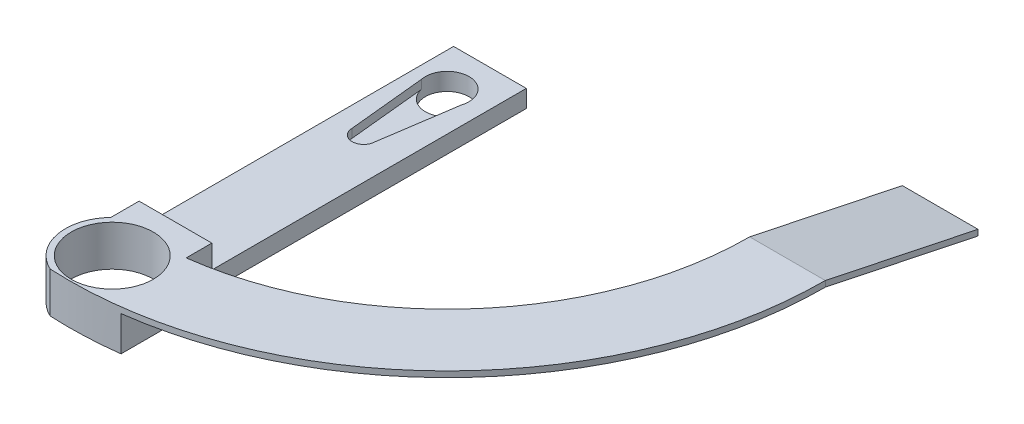
SolidWorks part; units mm, degrees
ref_plane "Front Plane" through (0, 0, 0) normal (0, 0, 1) x (1, 0, 0)
ref_plane "Top Plane" through (0, 0, 0) normal (0, 1, 0) x (1, 0, 0)
ref_plane "Right Plane" through (0, 0, 0) normal (1, 0, 0) x (0, 0, -1)
sketch "Sketch1" plane through (0, 0, 0) normal (0, 1, 0) x (1, 0, 0)
  line L4 (0, 0) -> (36.7696, -36.7696) construction
  line L6 (0, -63.5) -> (0, -51.6862) construction
  line L10 (6.6931, -1.4875) -> (6.6931, -51.5675)
  line L11 (-5.815, -3.0884) -> (-5.815, -52.0242)
  line L12 (-5.815, -3.0884) -> (-5.815, 3.9116)
  line L14 (6.6931, 3.9116) -> (6.6931, -1.4875)
  line L15 (45.9619, -45.9619) -> (61.1091, -61.1091) construction
  line L16 (48.0722, -19.8259) -> (60.0902, -24.7824)
  line L17 (6.6931, 3.9116) -> (6.6931, 6.9116)
  line L18 (6.6931, 6.9116) -> (-5.815, 6.9116)
  line L19 (-5.815, 6.9116) -> (-5.815, 3.9116)
  arc A0 (3.7159, -64.8937) -> (45.9619, -45.9619) centre (0, 0) ccw
  circle A2 centre (0, -57.5931) radius 7.0515
  arc A5 (-5.815, -52.0242) -> (-3.3524, -64.9135) centre (0, -57.5931) ccw
  arc A6 (36.7696, -36.7696) -> (6.6931, -51.5675) centre (0, 0) cw
  circle A7 centre (0, -57.5931) radius 8.0515 construction
  arc A8 (3.7159, -64.8937) -> (-3.3524, -64.9135) centre (0, 0) cw
  arc A9 (45.9619, -45.9619) -> (60.0902, -24.7824) centre (0, 0) ccw
  arc A10 (36.7696, -36.7696) -> (48.0722, -19.8259) centre (0, 0) ccw
  point P9 (0, 0)
  point P19 (0, 0)
  dimension "D1" = 1
extrude "Boss-Extrude1" add sketch "Sketch1" along normal blind 3
sketch "Sketch2" plane through (0, 3, 0) normal (0, 1, 0) x (1, 0, 0)
  line L2 (-5.815, -47.1607) -> (6.6931, -47.1607)
  line L4 (6.6931, -47.1607) -> (6.6931, -51.5675)
  line L6 (6.6931, -51.5675) -> (6.6931, 6.9116) construction
  line L7 (-5.815, -47.1607) -> (-5.815, -52.0242)
  line L8 (65, 0) -> (52, 0)
  arc A0 (-3.3524, -64.9135) -> (60.0902, -24.7824) centre (0, 0) ccw construction
  arc A1 (48.0722, -19.8259) -> (52, 0) centre (0, 0) ccw
  arc A2 (-3.3524, -64.9135) -> (60.0902, -24.7824) centre (0, 0) ccw
  circle A5 centre (0, -57.5931) radius 7.0515 construction
  circle A6 centre (0, -57.5931) radius 7.0515
  arc A7 (-5.815, -52.0242) -> (-3.3524, -64.9135) centre (0, -57.5931) ccw construction
  arc A8 (60.0902, -24.7824) -> (65, 0) centre (0, 0) ccw
  arc A9 (-5.815, -52.0242) -> (-3.3524, -64.9135) centre (0, -57.5931) ccw
  arc A10 (6.6931, -51.5675) -> (48.0722, -19.8259) centre (0, 0) ccw construction
  arc A11 (6.6931, -51.5675) -> (48.0722, -19.8259) centre (0, 0) ccw
  point P21 (0.4391, -47.1607)
extrude "Boss-Extrude2" add sketch "Sketch2" along normal blind 4
sketch "Sketch3" plane through (0, 3, 0) normal (0, 1, 0) x (1, 0, 0)
  circle A0 centre (0, 0) radius 3.75
sketch "Sketch4" plane through (0, 0, 0) normal (0, -1, 0) x (1, 0, 0)
  line L0 (0, -3.75) -> (0, 16) construction
  line L1 (3.75, 0) -> (1.65, 14)
  line L2 (-3.75, 0) -> (-2.35, 14)
  arc A0 (-3.75, 0) -> (3.75, 0) centre (0, 0) ccw
  arc A1 (1.65, 14) -> (-2.35, 14) centre (-0.35, 14) ccw
extrude "Cut-Extrude1" cut sketch "Sketch3" against normal through all
extrude "Cut-Extrude2" cut sketch "Sketch4" along normal blind 1.5 from offset 3 offset against normal yes
sketch "Sketch5" plane through (0, 0, 0) normal (0, -1, 0) x (1, 0, 0)
  line L1 (8.3839, 71.0017) -> (75.7106, 71.0017)
  line L2 (8.3839, 71.0017) -> (8.3839, -5.9997)
  line L3 (8.3839, -5.9997) -> (75.7106, -5.9997)
  line L4 (75.7106, 71.0017) -> (75.7106, -5.9997)
  point P4 (75.7106, -5.9997)
  point P5 (8.3839, 71.0017)
extrude "Cut-Extrude4" cut sketch "Sketch5" against normal blind 6
sketch "Sketch6" plane through (0, 6, 0) normal (0, -1, 0) x (1, 0, 0)
  line L1 (52, 0) -> (65, 0)
  line L2 (52, 0) -> (52, -26.2611)
  line L3 (52, -26.2611) -> (65, -26.2611)
  line L4 (65, 0) -> (65, -26.2611)
  dimension "D1" = 13
extrude "Boss-Extrude3" add sketch "Sketch6" along normal blind 10 and the other way blind 1
sketch "Sketch7" plane through (52, 0, 0) normal (-1, 0, 0) x (0, 0, 1)
  line L0 (0, 7) -> (-26.2611, 1.5)
  line L1 (-26.2611, 7) -> (-26.2611, -4) construction
  line L3 (-26.2611, 0.5) -> (0, 6)
  line L4 (-26.2611, 1.5) -> (-26.2611, 7)
  line L5 (0, 7) -> (-26.2611, 7) construction
  line L6 (-26.2611, 7) -> (0, 7)
  line L7 (-26.2611, 0.5) -> (-26.2611, -4)
  line L8 (-26.2611, -4) -> (0, -4)
  line L9 (0, -4) -> (0, 6)
extrude "Cut-Extrude5" cut sketch "Sketch7" against normal through all
